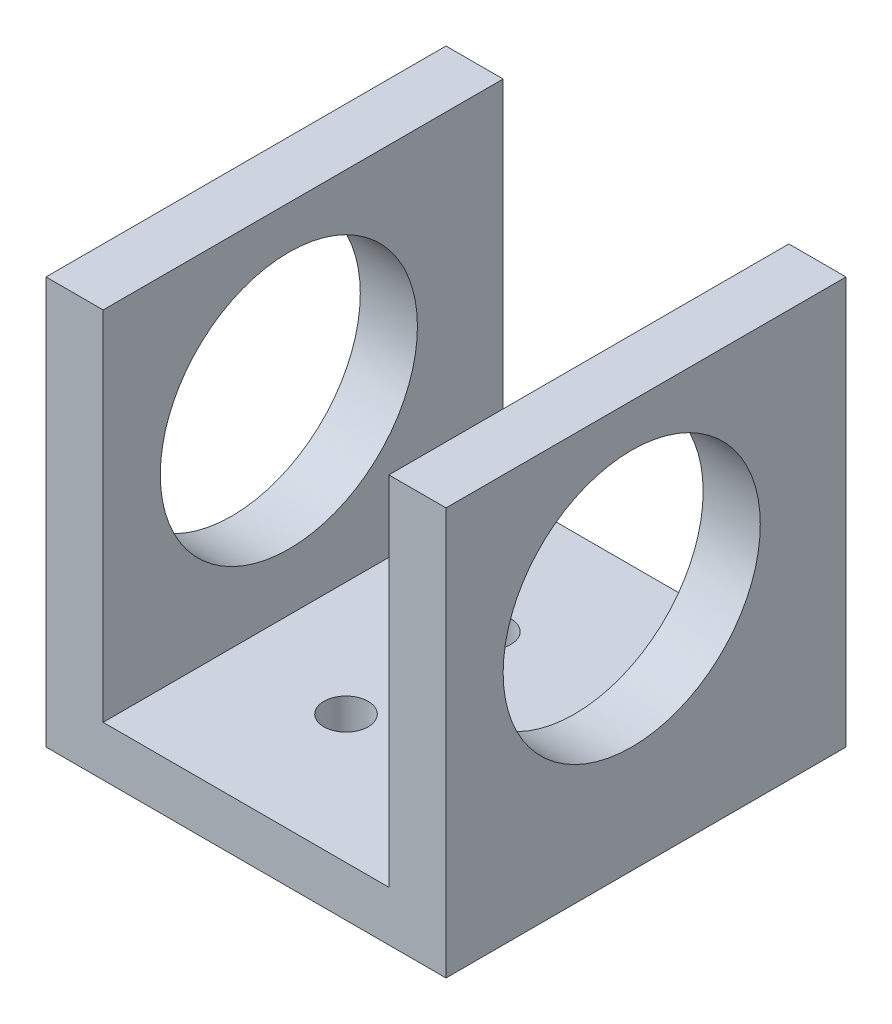
SolidWorks part; units mm, degrees
other "标注1"
sketch "草图5" plane through (0, 28.5, 28) normal (-0.0213, 0.9984, 0.0524) x (0.5856, -0.0301, 0.8101)
ref_plane "前视基准面" through (0, 0, 0) normal (0, 0, 1) x (1, 0, 0)
ref_plane "上视基准面" through (0, 0, 0) normal (0, 1, 0) x (1, 0, 0)
ref_plane "右视基准面" through (0, 0, 0) normal (1, 0, 0) x (0, 0, -1)
sketch "草图1" plane through (0, 0, 0) normal (0, 1, 0) x (1, 0, 0)
  line L1 (0, 0) -> (28, 0)
  line L2 (0, 0) -> (0, -28)
  line L3 (0, -28) -> (28, -28)
  line L4 (28, 0) -> (28, -28)
  dimension "D1" = 28
extrude "凸台-拉伸1" add sketch "草图1" along normal blind 3.5
sketch "草图2" plane through (0, 3.5, 0) normal (0, 1, 0) x (1, 0, 0)
  line L0 (0, -28) -> (28, -28) construction
  line L1 (0, 0) -> (4, 0)
  line L2 (0, 0) -> (0, -28)
  line L3 (0, -28) -> (4, -28)
  line L4 (4, 0) -> (4, -28)
  line L6 (28, 0) -> (24, 0)
  line L7 (28, 0) -> (28, -28)
  line L8 (28, -28) -> (24, -28)
  line L9 (24, 0) -> (24, -28)
  dimension "D1" = 4
  dimension "D2" = 4
extrude "凸台-拉伸2" add sketch "草图2" along normal blind 25
sketch "草图3" plane through (0, 0, 0) normal (-1, 0, 0) x (0, 0, 1)
  line L0 (0, 28.5) -> (0, 0) construction
  line L2 (0, 28.5) -> (28, 28.5) construction
  circle A0 centre (15, 16.5) radius 9
  dimension "D1" = 15
  dimension "D2" = 12
extrude "切除-拉伸1" cut sketch "草图3" against normal blind 50
sketch "草图4" plane through (0, 3.5, 0) normal (0, 1, 0) x (1, 0, 0)
  line L0 (24, 0) -> (4, 0) construction
  line L1 (4, -28) -> (24, -28) construction
  line L3 (24, 0) -> (24, -28) construction
  circle A0 centre (12, -19) radius 1.55
  circle A1 centre (12, -9) radius 1.55
  dimension "D1" = 9
  dimension "D4" = 3.1
  dimension "D2" = 9
  dimension "D3" = 12
extrude "切除-拉伸2" cut sketch "草图4" against normal blind 50
